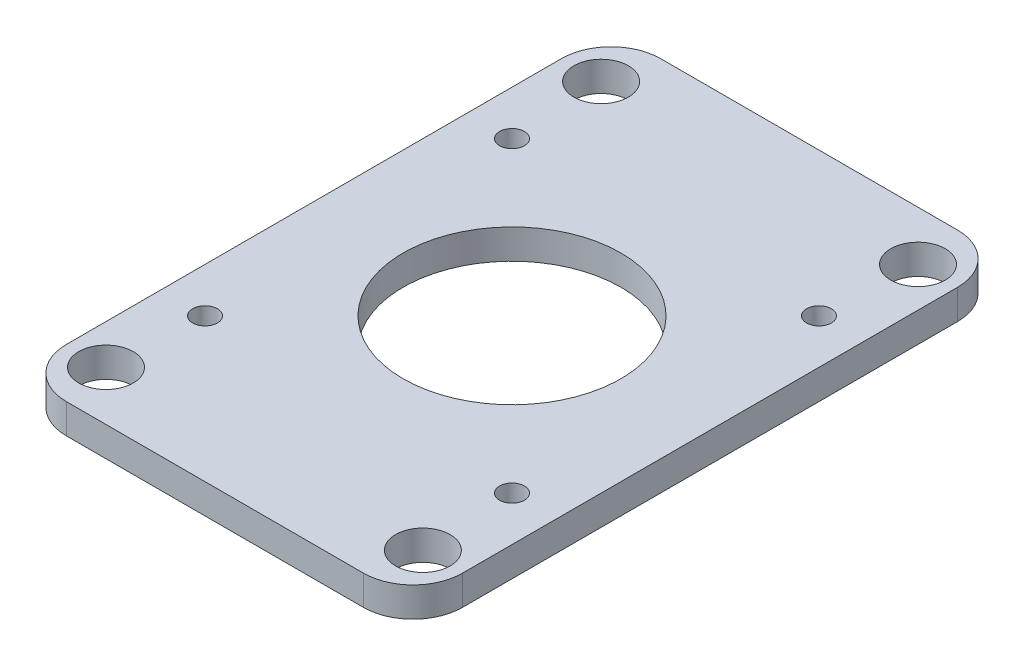
SolidWorks part; units mm, degrees
ref_plane "Plan de face" through (0, 0, 0) normal (0, 0, 1) x (1, 0, 0)
ref_plane "Plan de dessus" through (0, 0, 0) normal (0, 1, 0) x (1, 0, 0)
ref_plane "Plan de droite" through (0, 0, 0) normal (1, 0, 0) x (0, 0, -1)
sketch "Sketch1" plane through (0, 0, 0) normal (0, 1, 0) x (1, 0, 0)
  line L0 (0, 0) -> (0, 19.7452) construction
  line L1 (-16, 25) -> (16, 25) construction
  line L2 (-20, 30) -> (20, 30)
  line L3 (-20, 30) -> (-20, -30)
  line L4 (-15.5, 0) -> (15.5, 0) construction
  line L5 (15.5, 15.5) -> (-15.5, 15.5) construction
  line L6 (15.5, 15.5) -> (15.5, -15.5) construction
  line L7 (15.5, -15.5) -> (-15.5, -15.5) construction
  line L8 (-15.5, 15.5) -> (-15.5, -15.5) construction
  line L9 (15.5, 15.5) -> (-15.5, -15.5) construction
  line L10 (15.5, -15.5) -> (-15.5, 15.5) construction
  line L11 (0, -15.5) -> (0, 15.5) construction
  line L12 (-20, -30) -> (20, -30)
  line L13 (20, 30) -> (20, -30)
  line L14 (-16, -25) -> (16, -25) construction
  circle A0 centre (15.5, -15.5) radius 1.25
  circle A1 centre (15.5, 15.5) radius 1.25
  circle A2 centre (-15.5, 15.5) radius 1.25
  circle A3 centre (-15.5, -15.5) radius 1.25
  circle A4 centre (0, 0) radius 11
  circle A5 centre (0, 25) radius 4
  circle A6 centre (0, -25) radius 4
  circle A7 centre (-16, 25) radius 2.75
  circle A8 centre (16, 25) radius 2.75
  circle A9 centre (-16, -25) radius 2.75
  circle A10 centre (16, -25) radius 2.75
  point P4 (0, 0)
  point P26 (0, -30)
  point P27 (-20, 0)
  point P36 (0, 25)
  point P37 (0, -25)
  dimension "D1" = 2.5
  dimension "D2" = 2.5
  dimension "D3" = 2.5
  dimension "D4" = 2.5
  dimension "D7" = 22
  dimension "D8" = 8
  dimension "D14" = 5.5
  dimension "D15" = 5.5
  dimension "D16" = 5.5
  dimension "D17" = 5.5
  dimension "D5" = 31
  dimension "D6" = 31
  dimension "D9" = 25
  dimension "D10" = 40
  dimension "D11" = 60
  dimension "D12" = 32
  dimension "D13" = 32
extrude "Boss-Extrude1" add sketch "Sketch1" along normal blind 3 contours L13 L2 L3 L12 A10 A9 A8 A7 A0 A1 A2 A3 A4 A5 A6 | A5 | A6
fillet "Fillet1" radius 5 4 edges at (-20, 1.5, 30) (20, 1.5, 30) (20, 1.5, -30) (-20, 1.5, -30)
